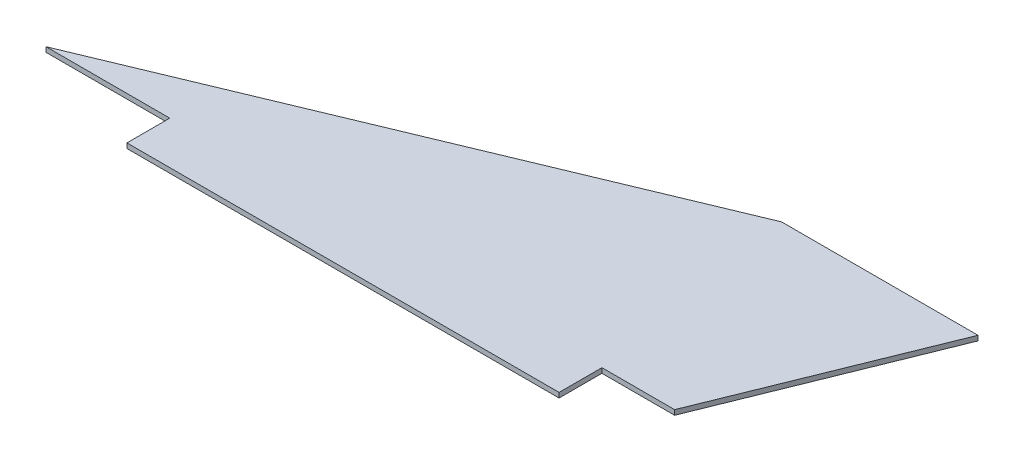
SolidWorks part; units mm, degrees
ref_plane "Front Plane" through (0, 0, 0) normal (0, 0, 1) x (1, 0, 0)
ref_plane "Top Plane" through (0, 0, 0) normal (0, 1, 0) x (1, 0, 0)
ref_plane "Right Plane" through (0, 0, 0) normal (1, 0, 0) x (0, 0, -1)
sketch "Sketch1" plane through (0, 0, 0) normal (0, 1, 0) x (1, 0, 0)
  line L0 (0, 0) -> (80.01, 0)
  line L1 (406.4, 0) -> (462.8425, 139.7)
  line L2 (462.8425, 139.7) -> (335.8425, 139.7)
  line L3 (335.8425, 139.7) -> (0, 0)
  line L4 (80.01, 0) -> (80.01, -27.686)
  line L5 (80.01, -27.686) -> (359.41, -27.686)
  line L6 (359.41, -27.686) -> (359.41, 0)
  line L7 (359.41, 0) -> (406.4, 0)
  dimension "D1" = 406.4
  dimension "D2" = 27.686
  dimension "D3" = 46.99
  dimension "D4" = 279.4
  dimension "D5" = 127
  dimension "D6" = 68
  dimension "D7" = 139.7
extrude "Boss-Extrude1" add sketch "Sketch1" along normal mid plane 3.175
